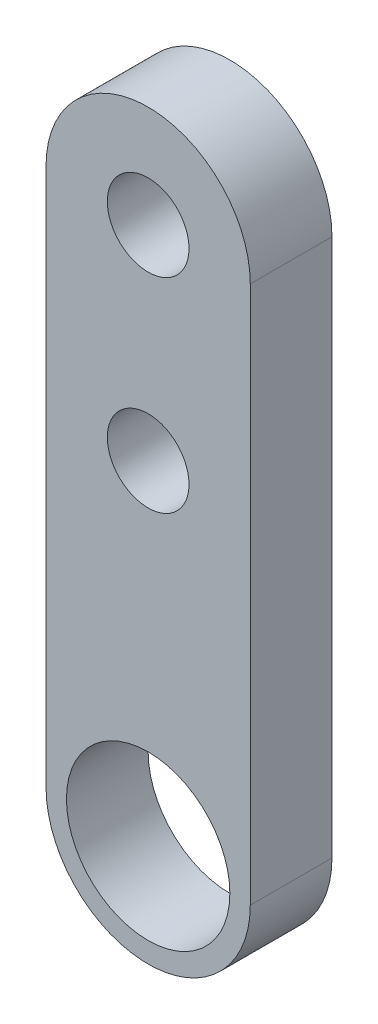
SolidWorks part; units mm, degrees
ref_plane "정면" through (0, 0, 0) normal (0, 0, 1) x (1, 0, 0)
ref_plane "윗면" through (0, 0, 0) normal (0, 1, 0) x (1, 0, 0)
ref_plane "우측면" through (0, 0, 0) normal (1, 0, 0) x (0, 0, -1)
sketch "스케치1" plane through (0, 0, 0) normal (0, 0, 1) x (1, 0, 0)
  line L3 (-2.5, 9.085) -> (-2.5, -4.085)
  line L5 (-2.5, 4.085) -> (2.5, -4.085) construction
  line L6 (-2.5, -4.085) -> (2.5, 4.085) construction
  line L7 (2.5, 9.085) -> (2.5, -4.085)
  arc A0 (2.5, 9.085) -> (-2.5, 9.085) centre (0, 9.085) ccw
  arc A1 (2.5, -4.085) -> (-2.5, -4.085) centre (0, -4.085) cw
  circle A2 centre (0, 4.085) radius 1
  circle A3 centre (0, -4.085) radius 2
  circle A4 centre (0, 9.085) radius 1
  point P0 (0, 0)
  point P10 (0, 9.085)
  dimension "D2" = 5
  dimension "D3" = 2
  dimension "D1" = 8.17
extrude "보스-돌출1" add sketch "스케치1" along normal blind 2
